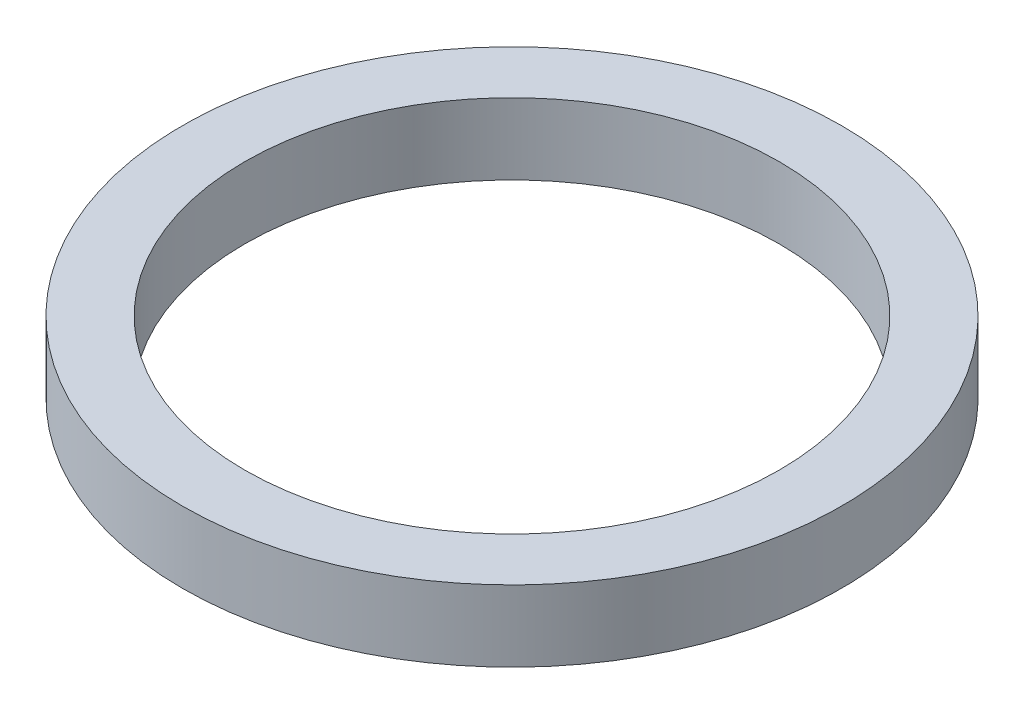
SolidWorks part; units mm, degrees
material "合金钢"
ref_plane "前视基准面" through (0, 0, 0) normal (0, 0, 1) x (1, 0, 0)
ref_plane "上视基准面" through (0, 0, 0) normal (0, 1, 0) x (1, 0, 0)
ref_plane "右视基准面" through (0, 0, 0) normal (1, 0, 0) x (0, 0, -1)
sketch "草图1" plane through (0, 0, 0) normal (0, 1, 0) x (1, 0, 0)
  circle A0 centre (0, 0) radius 18.5
  circle A1 centre (0, 0) radius 15
  dimension "D1" = 37
  dimension "D2" = 30
extrude "凸台-拉伸1" add sketch "草图1" along normal blind 4
